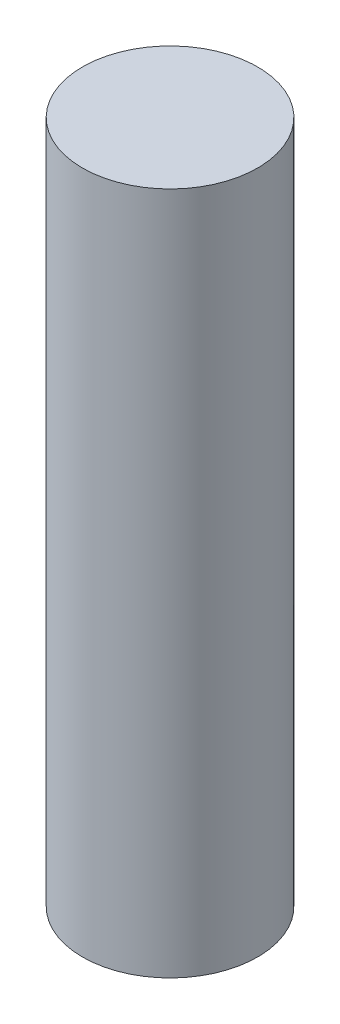
SolidWorks part; units mm, degrees
ref_plane "Alzado" through (0, 0, 0) normal (0, 0, 1) x (1, 0, 0)
ref_plane "Planta" through (0, 0, 0) normal (0, 1, 0) x (1, 0, 0)
ref_plane "Vista lateral" through (0, 0, 0) normal (1, 0, 0) x (0, 0, -1)
sketch "Croquis1" plane through (0, 0, 0) normal (0, 1, 0) x (1, 0, 0)
  circle A0 centre (0, 0) radius 100
  dimension "D1" = 200
extrude "Saliente-Extruir1" add sketch "Croquis1" along normal blind 780
